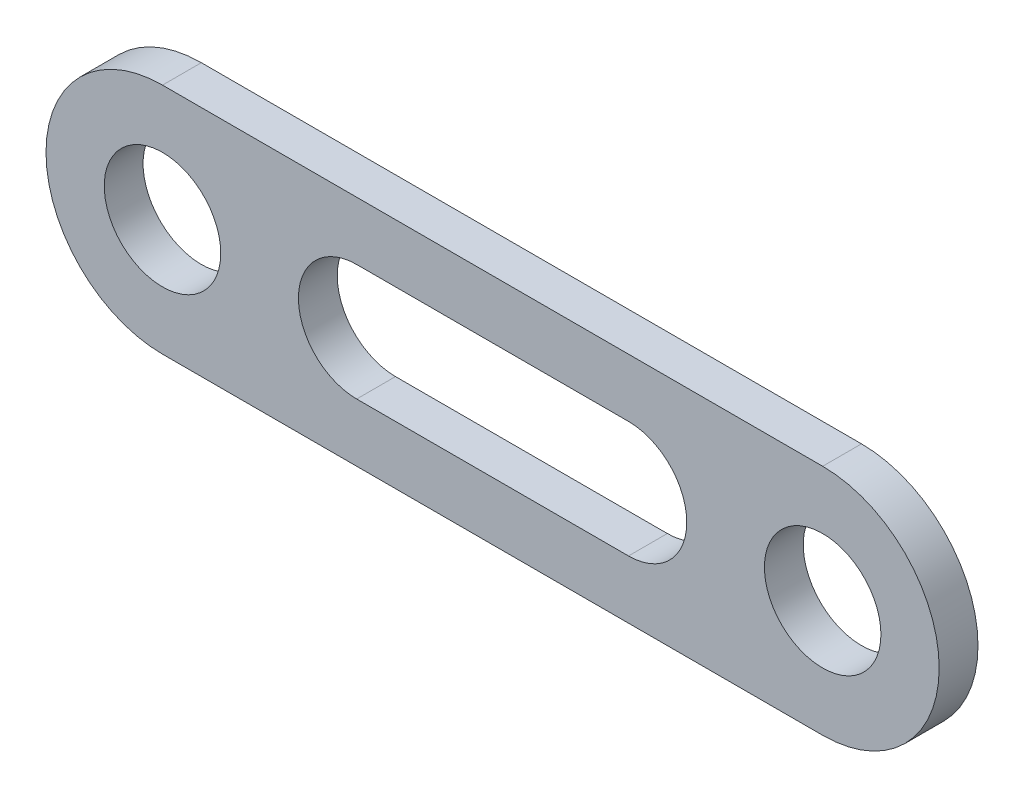
SolidWorks part; units mm, degrees
ref_plane "前视" through (0, 0, 0) normal (0, 0, 1) x (1, 0, 0)
ref_plane "上视" through (0, 0, 0) normal (0, 1, 0) x (1, 0, 0)
ref_plane "右视" through (0, 0, 0) normal (1, 0, 0) x (0, 0, -1)
sketch "草图2" plane through (0, 0, 0) normal (0, 0, 1) x (1, 0, 0)
  line L0 (0, 6) -> (34, 6)
  line L1 (0, -6) -> (34, -6)
  line L2 (10, 3) -> (24, 3)
  line L3 (10, -3) -> (24, -3)
  line L4 (-8.0174, 0) -> (37.0477, 0) construction
  arc A0 (0, 6) -> (0, -6) centre (0, 0) ccw
  arc A1 (34, -6) -> (34, 6) centre (34, 0) ccw
  circle A2 centre (0, 0) radius 3
  circle A3 centre (34, 0) radius 3
  arc A4 (10, 3) -> (10, -3) centre (10, 0) ccw
  arc A5 (24, -3) -> (24, 3) centre (24, 0) ccw
  dimension "D1" = 12
  dimension "D2" = 12
  dimension "D3" = 6
  dimension "D4" = 6
  dimension "D8" = 6
  dimension "D9" = 6
  dimension "D5" = 34
  dimension "D6" = 10
  dimension "D7" = 10
extrude "凸台-拉伸1" add sketch "草图2" along normal blind 2
